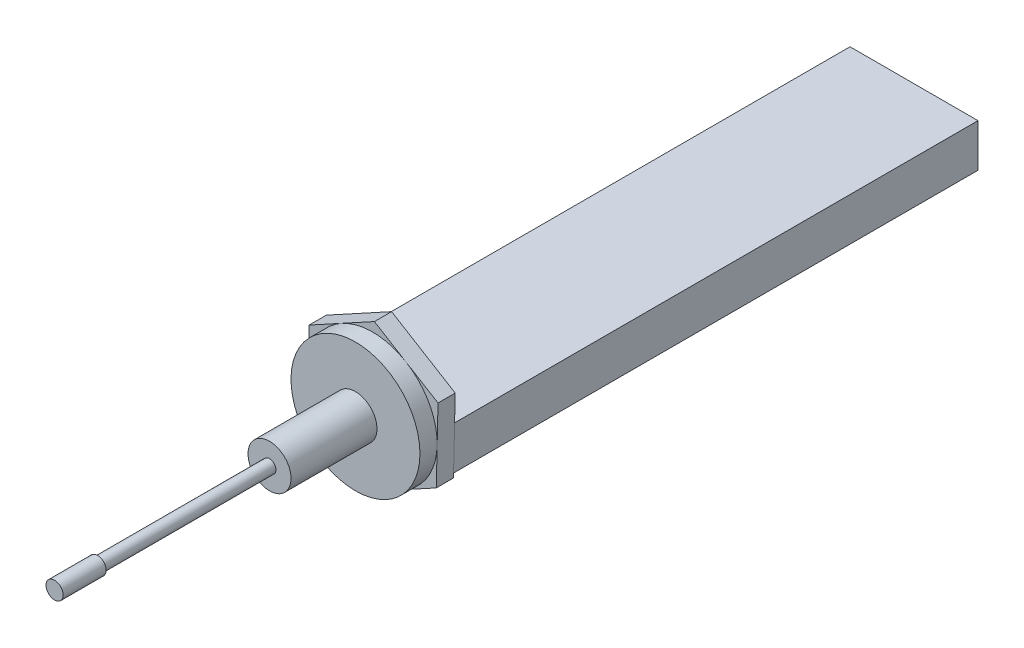
SolidWorks part; units mm, degrees
material "Copper"
ref_plane "Front Plane" through (0, 0, 0) normal (0, 0, 1) x (1, 0, 0)
ref_plane "Top Plane" through (0, 0, 0) normal (0, 1, 0) x (1, 0, 0)
ref_plane "Right Plane" through (0, 0, 0) normal (1, 0, 0) x (0, 0, -1)
sketch "Sketch1" plane through (0, 0, 0) normal (0, 0, 1) x (1, 0, 0)
  line L1 (7.3971, -4.5036) -> (7.5988, 4.1543)
  line L2 (7.5988, 4.1543) -> (0.2017, 8.6579)
  line L3 (0.2017, 8.6579) -> (-7.3971, 4.5036)
  line L4 (-7.3971, 4.5036) -> (-7.5988, -4.1543)
  line L5 (-7.5988, -4.1543) -> (-0.2017, -8.6579)
  line L6 (-0.2017, -8.6579) -> (7.3971, -4.5036)
  circle A1 centre (0, 0) radius 7.5 construction
  dimension "D2" = 15
extrude "Boss-Extrude1" add sketch "Sketch1" against normal blind 2
sketch "Sketch2" plane through (0, 0, 0) normal (0, 0, 1) x (1, 0, 0)
  circle A0 centre (0, 0) radius 7.5
  dimension "D1" = 15
extrude "Boss-Extrude2" add sketch "Sketch2" along normal blind 2
sketch "Sketch3" plane through (0, 0, 2) normal (0, 0, 1) x (1, 0, 0)
  circle A0 centre (0, 0) radius 2.5
  dimension "D1" = 5
extrude "Boss-Extrude3" add sketch "Sketch3" along normal blind 10
sketch "Sketch4" plane through (0, 0, 12) normal (0, 0, 1) x (1, 0, 0)
  circle A0 centre (0, 0) radius 0.75
  dimension "D1" = 1.5
extrude "Boss-Extrude4" add sketch "Sketch4" along normal blind 20
sketch "Sketch5" plane through (0, 0, 32) normal (0, 0, 1) x (1, 0, 0)
  circle A0 centre (0, 0) radius 1
  dimension "D1" = 2
extrude "Boss-Extrude5" add sketch "Sketch5" along normal blind 5
sketch "Sketch6" plane through (0, 0, -2) normal (0, 0, -1) x (-1, 0, 0)
  line L0 (-7.3971, -4.5036) -> (-7.5988, 4.1543) construction
  line L1 (-7.4089, -4) -> (7.4787, -4)
  line L2 (-7.4089, -4) -> (-7.4089, 1)
  line L3 (-7.4089, 1) -> (7.4787, 1)
  line L4 (7.4787, -4) -> (7.4787, 1)
  line L5 (7.3971, 4.5036) -> (7.5988, -4.1543) construction
  line L6 (0, 0) -> (0.0349, -4) construction
  dimension "D1" = 5
  dimension "D2" = 4
extrude "Boss-Extrude6" add sketch "Sketch6" along normal blind 61
